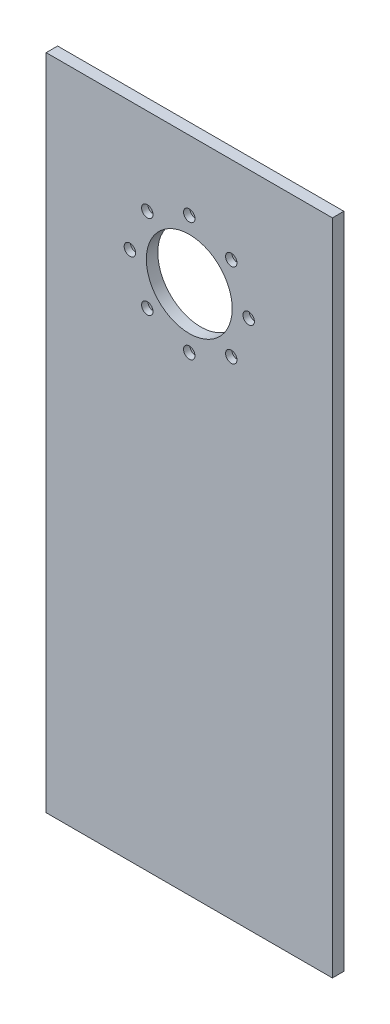
SolidWorks part; units mm, degrees
ref_plane "前视基准面" through (0, 0, 0) normal (0, 0, 1) x (1, 0, 0)
ref_plane "上视基准面" through (0, 0, 0) normal (0, 1, 0) x (1, 0, 0)
ref_plane "右视基准面" through (0, 0, 0) normal (1, 0, 0) x (0, 0, -1)
other "Configuration Table"
sketch "草图1" plane through (0, 0, 0) normal (0, 0, 1) x (1, 0, 0)
  line L0 (0, 0) -> (0, 498.031) construction
  line L1 (100, 0) -> (-100, 0)
  line L2 (-100, 0) -> (-100, 460)
  line L3 (-100, 460) -> (100, 460)
  line L4 (100, 0) -> (100, 460)
  point P7 (0, 460)
  dimension "D1" = 460
  dimension "D2" = 100
extrude "凸台-拉伸1" add sketch "草图1" along normal blind 8
sketch "草图2" plane through (0, 0, 0) normal (0, 0, -1) x (-1, 0, 0)
  line L0 (100, 0) -> (-100, 0) construction
  circle A0 centre (0, 370) radius 30
  circle A1 centre (0, 370) radius 81.25 construction
  dimension "D1" = 60
  dimension "D3" = 162.5
  dimension "D2" = 370
extrude "切除-拉伸1" cut sketch "草图2" against normal blind 10
sketch "草图3" plane through (0, 0, 0) normal (0, 0, -1) x (-1, 0, 0)
  line L0 (0, 370) -> (0, 473.0171) construction
  circle A0 centre (0, 370) radius 41.5 construction
  circle A1 centre (0, 411.5) radius 2.25
  circle A2 centre (29.3449, 399.3449) radius 2.25
  circle A3 centre (41.5, 370) radius 2.25
  circle A4 centre (29.3449, 340.6551) radius 2.25
  circle A5 centre (0, 328.5) radius 2.25
  circle A6 centre (-29.3449, 340.6551) radius 2.25
  circle A7 centre (-41.5, 370) radius 2.25
  circle A8 centre (-29.3449, 399.3449) radius 2.25
  point P23 (0, 370)
  dimension "D1" = 83
  dimension "D2" = 4.5
  dimension "D3" = 8
extrude "切除-拉伸2" cut sketch "草图3" against normal blind 10
sketch "草图4" plane through (0, 0, 8) normal (0, 0, 1) x (1, 0, 0)
  circle A0 centre (29.3449, 399.3449) radius 4
  circle A1 centre (41.5, 370) radius 4
  circle A2 centre (29.3449, 340.6551) radius 4
  circle A3 centre (0, 328.5) radius 4
  circle A4 centre (-29.3449, 340.6551) radius 4
  circle A5 centre (-41.5, 370) radius 4
  circle A6 centre (-29.3449, 399.3449) radius 4
  circle A7 centre (0, 411.5) radius 4
  point P19 (0, 370)
  dimension "D1" = 8
  dimension "D2" = 8
extrude "切除-拉伸3" cut sketch "草图4" against normal blind 4.4
